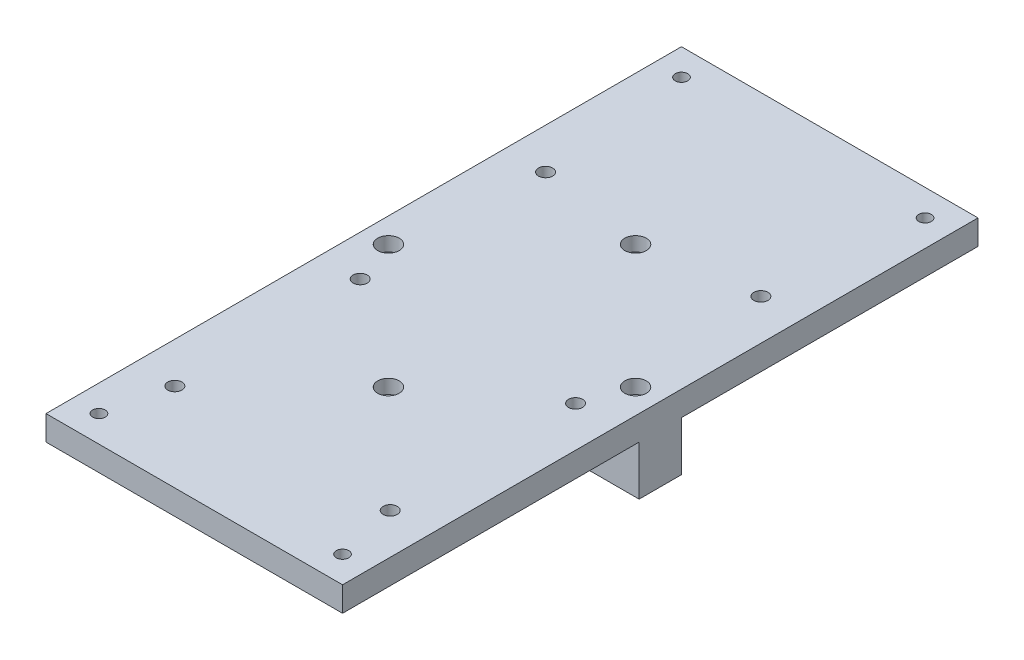
SolidWorks part; units mm, degrees
ref_plane "Front Plane" through (0, 0, 0) normal (0, 0, 1) x (1, 0, 0)
ref_plane "Top Plane" through (0, 0, 0) normal (0, 1, 0) x (1, 0, 0)
ref_plane "Right Plane" through (0, 0, 0) normal (1, 0, 0) x (0, 0, -1)
sketch "Sketch1" plane through (0, 0, 0) normal (0, 1, 0) x (1, 0, 0)
  line L1 (-47.4982, 91.081) -> (36.5018, 91.081)
  line L2 (-47.4982, 91.081) -> (-47.4982, -88.919)
  line L3 (-47.4982, -88.919) -> (36.5018, -88.919)
  line L4 (36.5018, 91.081) -> (36.5018, -88.919)
  dimension "D1" = 180
  dimension "D2" = 84
extrude "Boss-Extrude1" add sketch "Sketch1" along normal blind 7
sketch "Sketch2" plane through (0, 7, 0) normal (0, 1, 0) x (1, 0, 0)
  line L0 (-40.4982, -33.919) -> (-40.4982, 36.081) construction
  line L1 (-40.4982, 36.081) -> (29.5018, 36.081) construction
  line L2 (29.5018, 36.081) -> (29.5018, -33.919) construction
  line L3 (29.5018, -33.919) -> (-40.4982, -33.919) construction
  line L4 (-5.4982, -88.919) -> (-5.4982, 91.081) construction
  line L5 (-47.4982, -88.919) -> (36.5018, -88.919) construction
  line L6 (36.5018, 91.081) -> (-47.4982, 91.081) construction
  line L7 (-47.4982, 1.081) -> (36.5018, 1.081) construction
  line L8 (-47.4982, 91.081) -> (-47.4982, -88.919) construction
  line L9 (36.5018, -88.919) -> (36.5018, 91.081) construction
  circle A0 centre (-40.4982, 1.081) radius 1.775
  circle A1 centre (-5.4982, -33.919) radius 1.775
  circle A2 centre (29.5018, 1.081) radius 1.775
  circle A3 centre (-5.4982, 36.081) radius 1.775
  dimension "D4" = 3.55
  dimension "D1" = 70
  dimension "D2" = 35
  dimension "D3" = 35
extrude "Cut-Extrude1" cut sketch "Sketch2" against normal through all
sketch "Sketch3" plane through (0, 7, 0) normal (0, 1, 0) x (1, 0, 0)
  circle A0 centre (-40.4982, 1.081) radius 3.05
  circle A1 centre (-5.4982, -33.919) radius 3.05
  circle A2 centre (-5.4982, 36.081) radius 3.05
  circle A3 centre (29.5018, 1.081) radius 3.05
  circle A4 centre (-40.4982, 1.081) radius 1.775 construction
  circle A5 centre (-5.4982, -33.919) radius 1.775 construction
  circle A6 centre (-5.4982, 36.081) radius 1.775 construction
  circle A7 centre (29.5018, 1.081) radius 1.775 construction
  dimension "D1" = 6.1
extrude "Cut-Extrude2" cut sketch "Sketch3" against normal blind 4
sketch "Sketch5" plane through (0, 0, 0) normal (0, -1, 0) x (-1, 0, 0)
  line L0 (5.4982, -88.919) -> (5.4982, 91.081) construction
  line L1 (47.4982, -88.919) -> (-36.5018, -88.919) construction
  line L2 (-36.5018, 91.081) -> (47.4982, 91.081) construction
  line L3 (47.4982, 1.081) -> (-36.5018, 1.081) construction
  line L4 (47.4982, 91.081) -> (47.4982, -88.919) construction
  line L5 (-36.5018, -88.919) -> (-36.5018, 91.081) construction
  line L6 (47.4982, 91.081) -> (47.4982, -88.919) construction
  line L7 (11.4982, -39.919) -> (-0.5018, -39.919)
  line L8 (11.4982, -39.919) -> (11.4982, -27.919)
  line L9 (11.4982, -27.919) -> (-0.5018, -27.919)
  line L10 (-0.5018, -39.919) -> (-0.5018, -27.919)
  line L13 (47.4982, -4.919) -> (33.4982, -4.919)
  line L14 (47.4982, -4.919) -> (47.4982, 7.081)
  line L15 (11.4982, 30.081) -> (-0.5018, 30.081)
  line L16 (11.4982, 30.081) -> (11.4982, 42.081)
  line L17 (11.4982, 42.081) -> (-0.5018, 42.081)
  line L18 (-0.5018, 30.081) -> (-0.5018, 42.081)
  line L19 (-22.5018, -4.919) -> (-36.5018, -4.919)
  line L20 (-22.5018, -4.919) -> (-22.5018, 7.081)
  line L21 (-22.5018, 7.081) -> (-36.5018, 7.081)
  line L22 (-36.5018, -4.919) -> (-36.5018, 7.081)
  line L23 (11.4982, -33.919) -> (-0.5018, -33.919) construction
  line L24 (47.4982, 7.081) -> (33.4982, 7.081)
  line L25 (11.4982, 36.081) -> (-0.5018, 36.081) construction
  line L26 (5.4982, -27.919) -> (5.4982, -39.919) construction
  line L27 (-22.5018, 1.081) -> (-36.5018, 1.081) construction
  line L28 (5.4982, 42.081) -> (5.4982, 30.081) construction
  line L29 (33.4982, -4.919) -> (33.4982, 7.081)
  line L30 (-29.5018, 7.081) -> (-29.5018, -4.919) construction
  line L31 (40.4982, -4.919) -> (40.4982, 7.081) construction
  dimension "D1" = 12
  dimension "D2" = 35
  dimension "D4" = 35
  dimension "D5" = 70
extrude "Boss-Extrude2" add sketch "Sketch5" along normal blind 14
sketch "Sketch6" plane through (0, 7, 0) normal (0, 1, 0) x (1, 0, 0)
  circle A0 centre (-40.4982, 1.081) radius 1.775
  circle A1 centre (29.5018, 1.081) radius 1.775
  circle A2 centre (-5.4982, -33.919) radius 1.775
  circle A3 centre (-5.4982, 36.081) radius 1.775
  circle A4 centre (-40.4982, 1.081) radius 3.05 construction
  circle A5 centre (-5.4982, -33.919) radius 1.775 construction
  circle A6 centre (-5.4982, 36.081) radius 1.775 construction
  circle A7 centre (29.5018, 1.081) radius 3.05 construction
extrude "Cut-Extrude3" cut sketch "Sketch6" against normal through all
sketch "Sketch7" plane through (0, 7, 0) normal (0, 1, 0) x (1, 0, 0)
  line L0 (-35.9982, -63.919) -> (-35.9982, 41.081) construction
  line L1 (-35.9982, 41.081) -> (25.0018, 41.081) construction
  line L2 (25.0018, 41.081) -> (25.0018, -63.919) construction
  line L3 (25.0018, -63.919) -> (-35.9982, -63.919) construction
  line L4 (-47.4982, 41.081) -> (-35.9982, 41.081) construction
  line L5 (-47.4982, 91.081) -> (-47.4982, -88.919) construction
  line L6 (25.0018, 41.081) -> (36.5018, 41.081) construction
  line L7 (36.5018, -88.919) -> (36.5018, 91.081) construction
  line L10 (25.0018, 41.081) -> (25.0018, 91.081) construction
  line L11 (36.5018, 91.081) -> (-47.4982, 91.081) construction
  circle A0 centre (-35.9982, -63.919) radius 2
  circle A1 centre (-35.9982, -11.419) radius 2
  circle A2 centre (-35.9982, 41.081) radius 2
  circle A3 centre (25.0018, -63.919) radius 2
  circle A4 centre (25.0018, -11.419) radius 2
  circle A5 centre (25.0018, 41.081) radius 2
  dimension "D3" = 4
  dimension "D1" = 61
  dimension "D2" = 105
  dimension "D4" = 52.5
  dimension "D5" = 52.5
  dimension "D6" = 52.5
  dimension "D7" = 50
extrude "Cut-Extrude4" cut sketch "Sketch7" against normal through all
sketch "Sketch8" plane through (0, 7, 0) normal (0, 1, 0) x (1, 0, 0)
  line L0 (-39.9982, -81.419) -> (-39.9982, 83.581) construction
  line L1 (-39.9982, 83.581) -> (29.0018, 83.581) construction
  line L2 (29.0018, 83.581) -> (29.0018, -81.419) construction
  line L3 (29.0018, -81.419) -> (-39.9982, -81.419) construction
  line L4 (-47.4982, 91.081) -> (-47.4982, -88.919) construction
  line L5 (-47.4982, -88.919) -> (36.5018, -88.919) construction
  line L6 (36.5018, 91.081) -> (-47.4982, 91.081) construction
  line L7 (36.5018, -88.919) -> (36.5018, 91.081) construction
  circle A0 centre (-39.9982, -81.419) radius 1.775
  circle A1 centre (-39.9982, 83.581) radius 1.775
  circle A2 centre (29.0018, 83.581) radius 1.775
  circle A3 centre (29.0018, -81.419) radius 1.775
  dimension "D5" = 3.55
  dimension "D1" = 7.5
  dimension "D2" = 7.5
  dimension "D3" = 7.5
  dimension "D4" = 7.5
extrude "Cut-Extrude5" cut sketch "Sketch8" against normal through all
